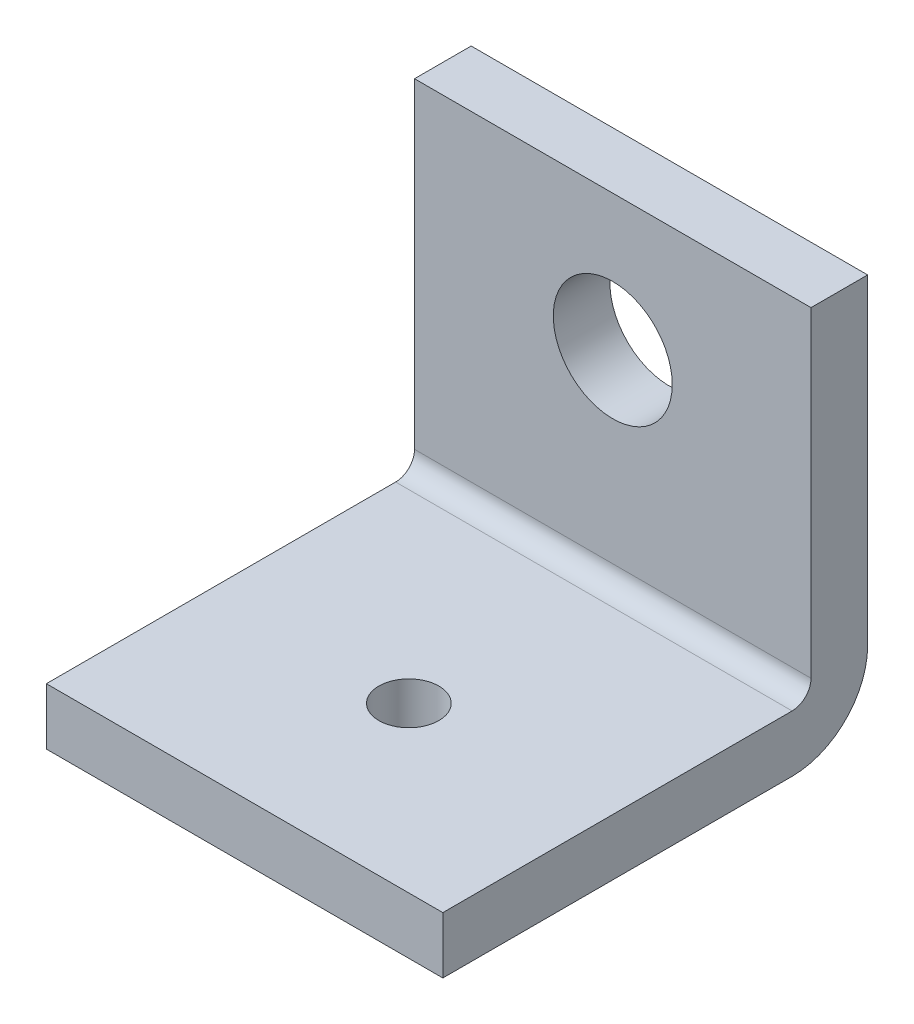
SolidWorks part; units mm, degrees
ref_plane "Front Plane" through (0, 0, 0) normal (0, 0, 1) x (1, 0, 0)
ref_plane "Top Plane" through (0, 0, 0) normal (0, 1, 0) x (1, 0, 0)
ref_plane "Right Plane" through (0, 0, 0) normal (1, 0, 0) x (0, 0, -1)
sketch "Sketch2" plane through (0, 0, 0) normal (1, 0, 0) x (0, 0, -1)
  line L0 (0, 4) -> (0, 21)
  line L1 (-4, 0) -> (-22.5, 0)
  line L2 (-4, 3) -> (-22.5, 3)
  line L3 (-3, 4) -> (-3, 21)
  line L4 (-3, 21) -> (0, 21)
  line L5 (-22.5, 0) -> (-22.5, 3)
  arc A0 (0, 4) -> (-4, 0) centre (-4, 4) cw
  arc A1 (-3, 4) -> (-4, 3) centre (-4, 4) cw
  point P6 (0, 0)
  dimension "D1" = 4
  dimension "D2" = 3
extrude "Extrude1" add sketch "Sketch2" along normal blind 21
sketch "Sketch3" plane through (0, 3, 0) normal (0, 1, 0) x (1, 0, 0)
  line L2 (10.5, -22.5) -> (10.5, -13.8) construction
  line L3 (10.5, -22.5) -> (10.5, -4) construction
  line L4 (21, -22.5) -> (0, -22.5) construction
  line L5 (21, -4) -> (0, -4) construction
  circle A0 centre (10.5, -13.8) radius 1.5875
extrude "Extrude2" cut sketch "Sketch3" against normal up to surface (3 mm away) up to face at (10.5, 0, 13.25)
sketch "Sketch4" plane through (0, 0, 3) normal (0, 0, 1) x (1, 0, 0)
  line L0 (10.5, 21) -> (10.5, 4) construction
  line L1 (21, 21) -> (0, 21) construction
  line L2 (21, 4) -> (0, 4) construction
  line L3 (10.5, 21) -> (10.5, 13.8) construction
  circle A0 centre (10.5, 13.8) radius 3.15
extrude "Extrude3" cut sketch "Sketch4" against normal up to surface (3 mm away) up to face at (10.5, 12.5, 0)
